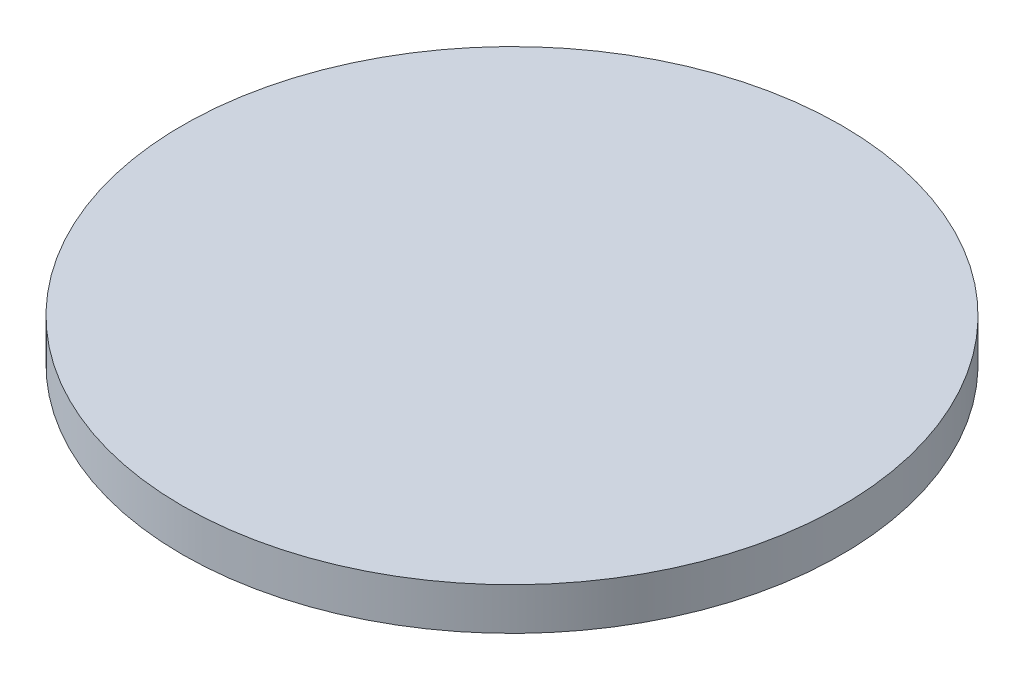
SolidWorks part; units mm, degrees
ref_plane "Front Plane" through (0, 0, 0) normal (0, 0, 1) x (1, 0, 0)
ref_plane "Top Plane" through (0, 0, 0) normal (0, 1, 0) x (1, 0, 0)
ref_plane "Right Plane" through (0, 0, 0) normal (1, 0, 0) x (0, 0, -1)
sketch "Sketch1" plane through (0, 0, 0) normal (0, 1, 0) x (1, 0, 0)
  circle A12 centre (0, 0) radius 62.5
  dimension "D1" = 125
sketch "Sketch2" plane through (0, 0, 0) normal (0, 1, 0) x (1, 0, 0)
  circle A1 centre (0, 0) radius 37.5 construction
  circle A2 centre (0, 0) radius 62.5
  circle A3 centre (0, 37.5) radius 11.25
  circle A4 centre (22.0419, 30.3381) radius 11.25
  circle A5 centre (35.6646, 11.5881) radius 11.25
  circle A6 centre (35.6646, -11.5881) radius 11.25
  circle A7 centre (22.0419, -30.3381) radius 11.25
  circle A8 centre (0, -37.5) radius 11.25
  circle A9 centre (-22.0419, -30.3381) radius 11.25
  circle A10 centre (-35.6646, -11.5881) radius 11.25
  circle A11 centre (-35.6646, 11.5881) radius 11.25
  circle A12 centre (-22.0419, 30.3381) radius 11.25
  circle A13 centre (0, 0) radius 25.25
  point P27 (0, 0)
  dimension "D1" = 75
  dimension "D2" = 22.5
  dimension "D4" = 50.5
  dimension "D5" = 125
  dimension "D3" = 10
extrude "Boss-Extrude1" add sketch "Sketch2" against normal blind 5
extrude "Boss-Extrude2" add sketch "Sketch1" along normal blind 3
